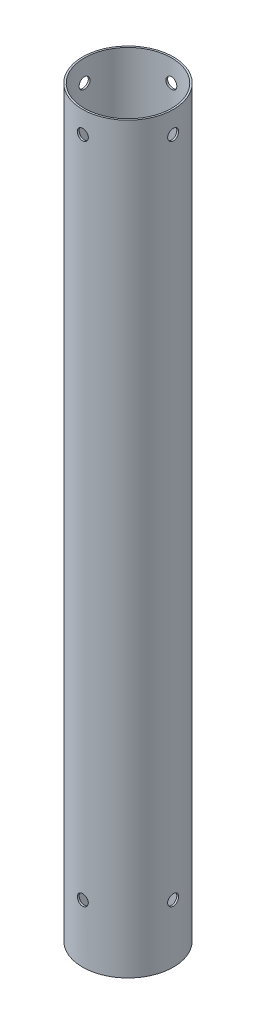
SolidWorks part; units mm, degrees
material "A-Glass Fiber"
ref_plane "Front Plane" through (0, 0, 0) normal (0, 0, 1) x (1, 0, 0)
ref_plane "Top Plane" through (0, 0, 0) normal (0, 1, 0) x (1, 0, 0)
ref_plane "Right Plane" through (0, 0, 0) normal (1, 0, 0) x (0, 0, -1)
sketch "Sketch1" plane through (0, 0, 0) normal (0, 1, 0) x (1, 0, 0)
  circle A0 centre (0, 0) radius 38.1
  circle A1 centre (0, 0) radius 39.624
  dimension "D1" = 76.2
  dimension "D2" = 79.248
extrude "Boss-Extrude1" add sketch "Sketch1" along normal blind 647.7
ref_plane "Plane1" through (39.624, 0, 0) normal (1, 0, 0) x (0, 0, -1)
sketch "Sketch2" plane through (39.624, 0, 0) normal (1, 0, 0) x (0, 0, -1)
  line L0 (0, 647.7) -> (0, 0)
  line L1 (39.624, 647.7) -> (-39.624, 647.7) construction
  line L2 (-39.624, 628.65) -> (39.624, 628.65)
  line L3 (-39.624, 647.7) -> (-39.624, 0) construction
  line L4 (39.624, 0) -> (39.624, 647.7) construction
  line L5 (-39.624, 50.8) -> (39.624, 50.8)
  line L6 (38.1, 647.7) -> (-38.1, 647.7) construction
  line L7 (-39.624, 0) -> (39.624, 0) construction
  circle A0 centre (0, 628.65) radius 4.7625
  circle A1 centre (0, 50.8) radius 4.7625
  dimension "D1" = 19.05
  dimension "D2" = 50.8
extrude "Cut-Extrude1" cut sketch "Sketch2" against normal through all contours L2 A0 L0 | L0 A0 L2 | L2 A0 L0 | L0 A0 L2 | L0 A1 L5 | L5 A1 L0 | L0 A1 L5 | L5 A1 L0
pattern_circular "CirPattern1" count 4 over 360 about axis through (0, 647.7, 0) along (0, -1, 0) of "Cut-Extrude1"
